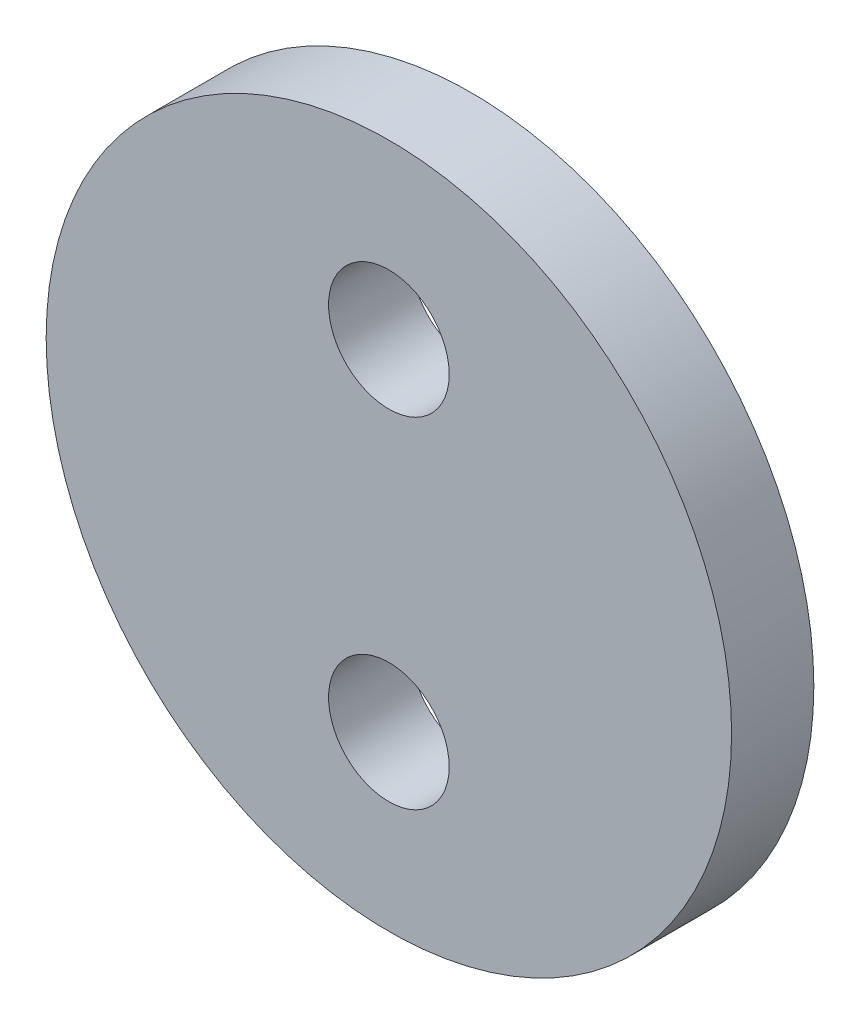
SolidWorks part; units mm, degrees
material "ABS"
ref_plane "前视基准面" through (0, 0, 0) normal (0, 0, 1) x (1, 0, 0)
ref_plane "上视基准面" through (0, 0, 0) normal (0, 1, 0) x (1, 0, 0)
ref_plane "右视基准面" through (0, 0, 0) normal (1, 0, 0) x (0, 0, -1)
sketch "草图1" plane through (0, 0, 0) normal (0, 0, 1) x (1, 0, 0)
  circle A0 centre (0, 0) radius 12.5
  circle A1 centre (0, 0) radius 6.2 construction
  circle A2 centre (0, 6.2) radius 2.2
  circle A3 centre (0, -6.2) radius 2.2
  dimension "D1" = 4.4
  dimension "D2" = 4.4
  dimension "D3" = 25
  dimension "D4" = 12.4
extrude "凸台-拉伸1" add sketch "草图1" along normal blind 3
